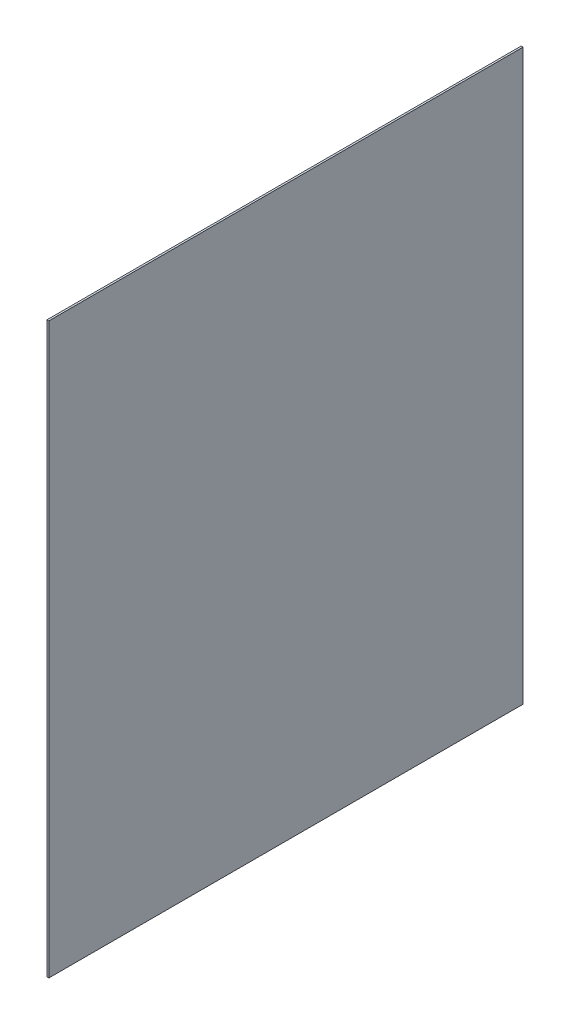
SolidWorks part; units mm, degrees
ref_plane "Front Plane" through (0, 0, 0) normal (0, 0, 1) x (1, 0, 0)
ref_plane "Top Plane" through (0, 0, 0) normal (0, 1, 0) x (1, 0, 0)
ref_plane "Right Plane" through (0, 0, 0) normal (1, 0, 0) x (0, 0, -1)
sketch "Sketch1" plane through (0, 0, 0) normal (0, 0, 1) x (1, 0, 0)
  line L0 (0, 1500) -> (0, -1500)
  line L1 (5, -1500) -> (-5, -1500)
  line L2 (5, -1500) -> (5, 1500)
  line L4 (5, 1500) -> (-5, 1500)
  line L5 (-5, -1500) -> (-5, 1500)
  line L6 (5, 0) -> (-5, 0)
  point P12 (0, 0)
  dimension "D1" = 10
  dimension "D2" = 1500
  dimension "D3" = 1500
extrude "Boss-Extrude1" add sketch "Sketch1" along normal blind 2500 contours L5 L4 L2 L1
